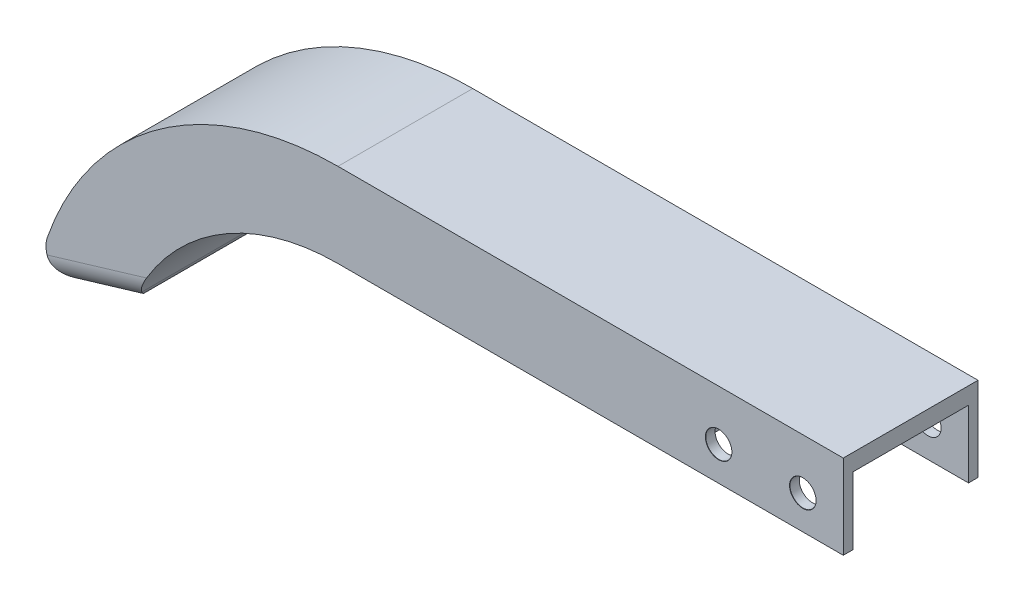
SolidWorks part; units mm, degrees
ref_plane "Front Plane" through (0, 0, 0) normal (0, 0, 1) x (1, 0, 0)
ref_plane "Top Plane" through (0, 0, 0) normal (0, 1, 0) x (1, 0, 0)
ref_plane "Right Plane" through (0, 0, 0) normal (1, 0, 0) x (0, 0, -1)
sketch "Sketch1" plane through (0, 0, 0) normal (0, 1, 0) x (1, 0, 0)
  line L1 (-30, 8) -> (30, 8)
  line L2 (-30, 8) -> (-30, -8)
  line L3 (-30, -8) -> (30, -8)
  line L4 (30, 8) -> (30, -8)
  line L5 (-30, 8) -> (30, -8) construction
  line L6 (-30, -8) -> (30, 8) construction
  point P0 (0, 0)
  dimension "D1" = 16
  dimension "D2" = 60
extrude "Boss-Extrude1" add sketch "Sketch1" along normal blind 10
sketch "Sketch3" plane through (0, 0, 0) normal (0, 1, 0) x (1, 0, 0)
  line L0 (30, -8) -> (30, 8) construction
  line L1 (30, -6.873) -> (9.746, -6.873)
  line L2 (30, -6.873) -> (30, 6.873)
  line L3 (30, 6.873) -> (9.746, 6.873)
  line L4 (9.746, -6.873) -> (9.746, 6.873)
  point P6 (9.746, 0)
  point P12 (30, 0)
  dimension "D1" = 13.746
  dimension "D2" = 20.254
extrude "Cut-Extrude1" cut sketch "Sketch3" along normal blind 8
sketch "Sketch4" plane through (0, 0, 8) normal (0, 0, 1) x (1, 0, 0)
  line L0 (15.2, 4) -> (25.2, 4) construction
  line L4 (9.746, 0) -> (30, 0)
  line L5 (9.746, 8) -> (9.746, 0)
  line L6 (30, 8) -> (9.746, 8)
  line L7 (30, 0) -> (30, 8)
  line L9 (9.746, 8) -> (9.746, 0) construction
  line L10 (30, 8) -> (9.746, 8) construction
  line L11 (30, 0) -> (30, 8) construction
  line L13 (9.746, 0) -> (30, 0)
  circle A0 centre (25.2, 4) radius 1.377
  circle A1 centre (15.2, 4) radius 1.377
  point P6 (20.2, 4)
  point P10 (9.746, 4)
  dimension "D2" = 2.754
  dimension "D3" = 10
  dimension "D4" = 4.8
  dimension "D1" = 0
sketch "Sketch6" plane through (0, 0, 8) normal (0, 0, 1) x (1, 0, 0)
  line L0 (-30, 10) -> (-30, 0) construction
  line L1 (-30, 0) -> (-16.2624, 2.6977)
  line L2 (-30, 0) -> (-30, -16.0269)
  line L3 (-30, -16.0269) -> (-12.5854, -16.0269)
  line L4 (-16.2624, 2.6977) -> (-12.5854, -16.0269)
  dimension "D1" = 101.11
  dimension "D2" = 14
  dimension "D3" = 90
extrude "Cut-Extrude3" [suppressed] cut sketch "Sketch6" against normal through all
sketch "Sketch9" [suppressed] plane through (0, 0, 8) normal (0, 0, 1) x (1, 0, 0)
  line L1 (-25.7326, 0) -> (-25.5531, -0.9142)
  line L7 (-25.5531, -0.9142) -> (-15.3096, 0)
  line L8 (-25.7326, 0) -> (40, 0) construction
  line L9 (-15.3096, 0) -> (-25.7326, 0)
  line L10 (-26.2624, 2.6977) -> (-25.7326, 0) construction
  dimension "D1" = 96.01
extrude "Boss-Extrude3" [suppressed] add sketch "Sketch9" against normal up to surface (16 mm away)
sketch "Sketch7" plane through (0, 10, 0) normal (0, 1, 0) x (1, 0, 0)
  line L1 (30, 8) -> (-30, 8) construction
  line L2 (7.2698, 8) -> (-30, 8) construction
  line L3 (-30, 8) -> (-30, -8) construction
  line L4 (-30, 8) -> (-30, 2.8227) construction
  line L5 (7.2698, 8) -> (-30, 8)
  line L6 (-30, 8) -> (-30, 2.8227)
  spline S0 degree 2 poles (7.2698, 8) (-30, 8) (-30, 2.8227) knots 0 0 0 1 1 1
extrude "Cut-Extrude6" [suppressed] cut sketch "Sketch7" against normal through all
mirror "Mirror2" [suppressed] about plane through (0, 0, 0) normal (0, 0, 1)
hole_wizard "M2.5 Clearance Hole1" positions "Sketch10" profile "Sketch11" hole size "M2.5" standard "ANSI Metric" end condition through all
sketch "Sketch10" plane through (0, 0, 8) normal (0, 0, 1) x (1, 0, 0)
  point P0 (15.2, 4)
  point P3 (25.2, 4)
sketch "Sketch11" plane through (15.2, 4, 8) normal (1, 0, 0) x (0, -1, 0)
  line L0 (0, 0) -> (0, 16)
  line L1 (0, 16) -> (1.55, 16)
  line L2 (1.55, 16) -> (1.55, 0.025)
  line L3 (1.55, 0.025) -> (1.575, 0)
  line L5 (1.575, 0) -> (0, 0)
  line L6 (-1.55, 0.025) -> (-1.575, 0) construction
  line L11 (0, -6.35) -> (0, 107.95) construction
  dimension "Thru Hole Dia." = 3.1
  dimension "Thru Hole Depth" = 16
  dimension "Near C'Sink Dia." = 3.15
  dimension "Near C'Sink Angle" = 90
ref_plane "Plane1" through (0, -25, 0) normal (0, -1, 0) x (-1, 0, 0)
sketch "Sketch12" plane through (0, 10, 0) normal (0, 1, 0) x (1, 0, 0)
  line L0 (-30, 8) -> (-103.5502, 7.9999)
  line L1 (-103.5502, 7.9999) -> (-103.5502, 0)
  line L4 (-103.5502, 0) -> (-103.5502, -8)
  line L5 (-103.5502, -8) -> (-30, -8)
  line L7 (-30, -8) -> (30, -8) construction
  line L11 (30, -8) -> (30, 8)
  line L12 (30, 8) -> (-30, 8)
  line L13 (-30, 8) -> (-30, -8)
  line L14 (-30, -8) -> (30, -8)
  line L17 (-30, 8) -> (-30, -8)
  point P0 (-102.9346, 0)
  dimension "D2" = 0
extrude "Boss-Extrude4" add sketch "Sketch12" against normal up to surface (35 mm away) up to plane "Plane1"
sketch "Sketch14" plane through (0, 0, 0) normal (0, 0, 1) x (1, 0, 0)
  line L1 (30, 0) -> (-30, 0) construction
  line L2 (-55.7237, -16.8777) -> (-63.6758, -19.2575) construction
  line L3 (30, 0) -> (-30, 0)
  line L4 (30, 10) -> (-30, 10) construction
  line L5 (30, 10) -> (-30, 10)
  line L9 (30, 10) -> (30, 0) construction
  line L10 (30, 10) -> (30, 0)
  line L12 (-54.5751, -16.534) -> (-65.9296, -19.932)
  line L13 (-30, 10) -> (-30, 0) construction
  arc A0 (-30, 0) -> (-54.5751, -16.534) centre (-30, -26.5305) ccw
  arc A1 (-30, 10) -> (-65.9296, -19.932) centre (-30, -26.5305) ccw
extrude "Cut-Extrude8" cut sketch "Sketch14" against normal through all both and the other way through all flip side to cut
fillet "Fillet1" [suppressed] radius 10
fillet "Fillet2" [suppressed] radius 1
fillet "Fillet3" [suppressed] radius 3
fillet "Fillet6" radius 3 4 edges at (-54.5751, -16.534, 0) (-60.2523, -18.233, -8) (-65.9296, -19.932, 0) (-60.2523, -18.233, 8)
